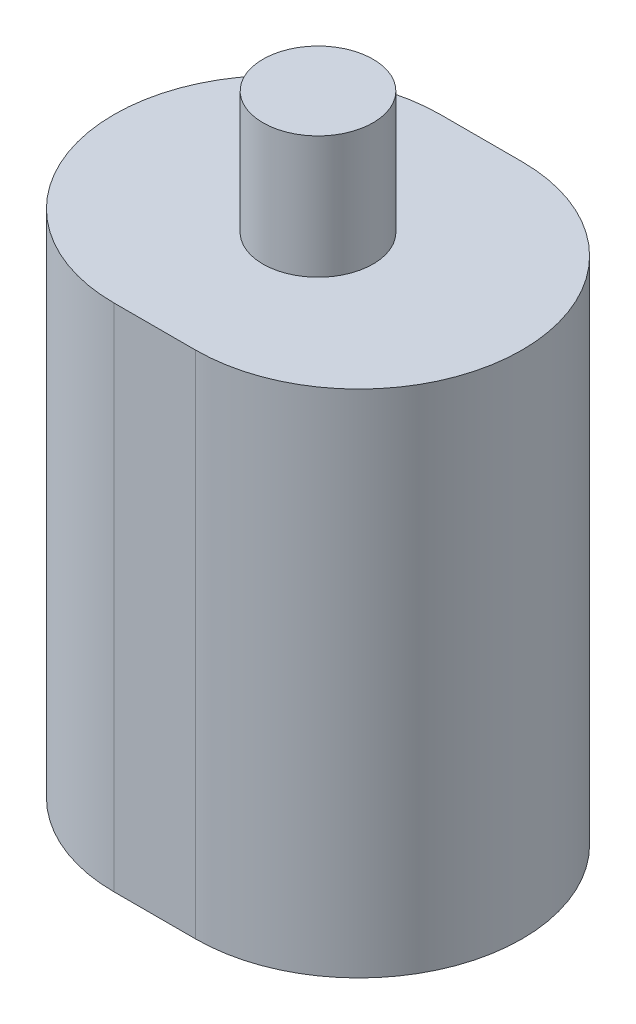
SolidWorks part; units mm, degrees
ref_plane "Plan de face" through (0, 0, 0) normal (0, 0, 1) x (1, 0, 0)
ref_plane "Plan de dessus" through (0, 0, 0) normal (0, 1, 0) x (1, 0, 0)
ref_plane "Plan de droite" through (0, 0, 0) normal (1, 0, 0) x (0, 0, -1)
sketch "Esquisse1" plane through (0, 0, 0) normal (0, 1, 0) x (1, 0, 0)
  line L0 (4, 0) -> (4, 8) construction
  line L1 (0, 0) -> (10, 0)
  line L2 (0, 0) -> (0, 8)
  line L3 (0, 8) -> (10, 8)
  line L4 (10, 0) -> (10, 8)
  line L6 (6, 0) -> (6, 8) construction
  arc A0 (4, 0) -> (4, 8) centre (4, 4) cw
  arc A1 (6, 0) -> (6, 8) centre (6, 4) ccw
  dimension "D1" = 10
  dimension "D2" = 8
extrude "Boss.-Extru.1" add sketch "Esquisse1" along normal blind 12.5 contours L1 A1 L3 A0
sketch "Esquisse2" plane through (0, 12.5, 0) normal (0, 1, 0) x (1, 0, 0)
  line L0 (0, 0) -> (10, 0) construction
  line L1 (10, 0) -> (10, 8) construction
  line L2 (10, 8) -> (0, 0) construction
  line L3 (6, 8) -> (10, 8) construction
  circle A0 centre (5, 4) radius 1.35
  arc A1 (6, 0) -> (6, 8) centre (6, 4) ccw construction
  point P10 (0, 0)
  dimension "D1" = 2.7
extrude "Boss.-Extru.2" add sketch "Esquisse2" along normal blind 3
